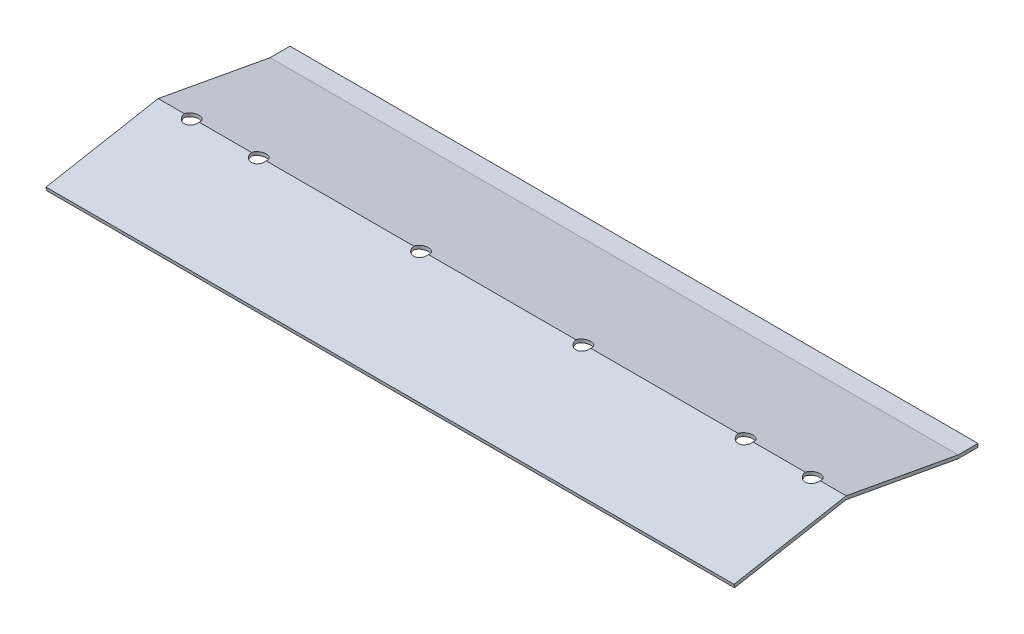
SolidWorks part; units mm, degrees
material "ASTM A36 Steel"
ref_plane "Front Plane" through (0, 0, 0) normal (0, 0, 1) x (1, 0, 0)
ref_plane "Top Plane" through (0, 0, 0) normal (0, 1, 0) x (1, 0, 0)
ref_plane "Right Plane" through (0, 0, 0) normal (1, 0, 0) x (0, 0, -1)
sketch "Sketch1" plane through (0, 0, 0) normal (1, 0, 0) x (0, 0, -1)
  line L0 (-5649.1389, -1238.6897) -> (-5481.8306, -1208.0054)
  line L1 (-5481.8306, -1208.0054) -> (-5314.9238, -1238.6239)
  line L2 (-5314.9238, -1238.6239) -> (-5285.3306, -1238.6239)
  line L3 (-5285.3306, -1238.6239) -> (-5285.3306, -1243.6239)
  line L4 (-5285.3306, -1243.6239) -> (-5315.3306, -1243.6239)
  line L5 (-5315.3306, -1243.6239) -> (-5481.8306, -1213.072)
  line L6 (-5481.8306, -1213.072) -> (-5648.3306, -1243.6239)
  line L7 (-5648.3306, -1243.6239) -> (-5649.1389, -1238.6897)
extrude "Boss-Extrude1" add sketch "Sketch1" along normal blind 1026
sketch "Sketch2" plane through (0, 0, 0) normal (0, 1, 0) x (1, 0, 0)
  line L0 (1026, -5481.8306) -> (0, -5481.8306) construction
  line L1 (0, -5481.8306) -> (0, -5649.1389) construction
  line L2 (1026, -5481.8306) -> (1026, -5649.1389) construction
  circle A0 centre (50, -5481.8306) radius 11
  circle A1 centre (150, -5481.8306) radius 11
  circle A2 centre (976, -5481.8306) radius 11
  circle A3 centre (876, -5481.8306) radius 11
  circle A4 centre (634, -5481.8306) radius 11
  circle A6 centre (392, -5481.8306) radius 11
  dimension "D1" = 22
  dimension "D2" = 50
  dimension "D3" = 22
  dimension "D4" = 100
  dimension "D5" = 22
  dimension "D6" = 50
  dimension "D7" = 22
  dimension "D8" = 100
  dimension "D9" = 22
  dimension "D10" = 242
  dimension "D11" = 22
  dimension "D12" = 242
extrude "Cut-Extrude1" cut sketch "Sketch2" against normal through all both and the other way through all
